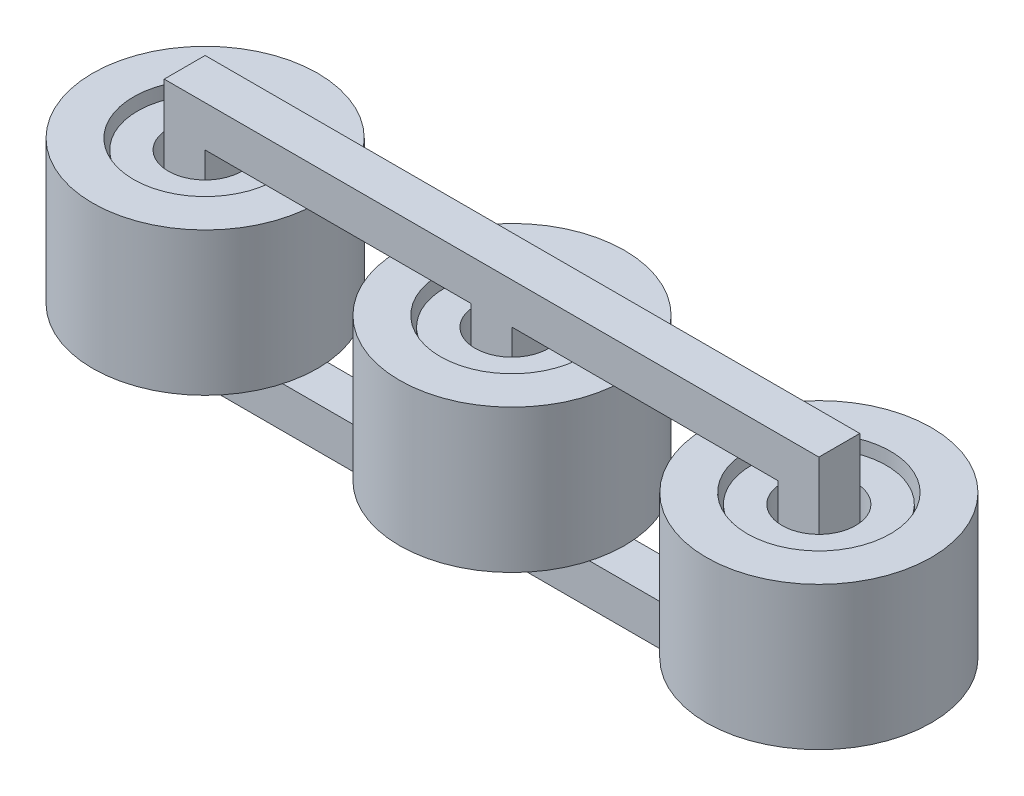
SolidWorks part; units mm, degrees
ref_plane "Front Plane" through (0, 0, 0) normal (0, 0, 1) x (1, 0, 0)
ref_plane "Top Plane" through (0, 0, 0) normal (0, 1, 0) x (1, 0, 0)
ref_plane "Right Plane" through (0, 0, 0) normal (1, 0, 0) x (0, 0, -1)
ref_axis "Axis1" through (0, 717.9002, 0) along (0, -1, 0)
sketch "Sketch2" plane through (0, 0, 0) normal (0, 0, 1) x (1, 0, 0)
  line L0 (0, 54.1789) -> (0, -55) construction
  line L1 (-1500, 500) -> (0, 500) construction
  line L2 (-1500, 500) -> (-1500, -500) construction
  line L3 (-1500, -500) -> (0, -500) construction
  line L4 (0, 500) -> (0, -500) construction
  line L5 (-1600, 600) -> (100, 600)
  line L6 (100, 600) -> (100, -600)
  line L7 (-1600, -600) -> (100, -600)
  line L8 (-1600, 600) -> (-1600, -600)
  line L9 (-1400, 400) -> (-100, 400)
  line L10 (-100, 400) -> (-100, -400)
  line L11 (-1400, -400) -> (-100, -400)
  line L12 (-1400, 400) -> (-1400, -400)
  dimension "D1" = 1000
  dimension "D2" = 1500
  dimension "D3" = 100
  dimension "D4" = 100
extrude "Boss-Extrude1" add sketch "Sketch2" along normal mid plane 200
sketch "Sketch4" plane through (0, 0, 0) normal (0, 0, 1) x (1, 0, 0)
  line L0 (0, 717.9002) -> (0, -688.738) construction
  line L1 (180, 300) -> (330, 300)
  line L2 (180, 300) -> (180, -300)
  line L3 (180, -300) -> (330, -300)
  line L4 (330, 300) -> (330, -300)
  point P4 (180, 0)
  dimension "D1" = 150
  dimension "D2" = 600
  dimension "D3" = 180
revolve "Primary winding" add sketch "Sketch4" angle 360 about axis through (0, 717.9002, 0) along (0, -1, 0)
sketch "Sketch5" plane through (0, 0, 0) normal (0, 0, 1) x (1, 0, 0)
  line L1 (350, 350) -> (550, 350)
  line L2 (350, 350) -> (350, -350)
  line L3 (350, -350) -> (550, -350)
  line L4 (550, 350) -> (550, -350)
  line L5 (330, -300) -> (330, 300) construction
  point P4 (350, 0)
  dimension "D1" = 200
  dimension "D2" = 700
  dimension "D3" = 20
revolve "Secondary winding" add sketch "Sketch5" angle 360 about axis through (0, 717.9002, 0) along (0, -1, 0)
pattern_linear "LPattern2" count 2 spacing 1500 along (-1, 0, 0) of bodies 106 107
mirror "Mirror3" about plane through (0, 0, 0) normal (1, 0, 0) of "Boss-Extrude1"
mirror "Mirror4" about plane through (0, 0, 0) normal (1, 0, 0) of bodies 109 108
equation "\"D4@Sketch2\"=\"D1@Boss-Extrude1\"/2"
equation "\"D3@Sketch2\"=\"D1@Boss-Extrude1\"/2"
